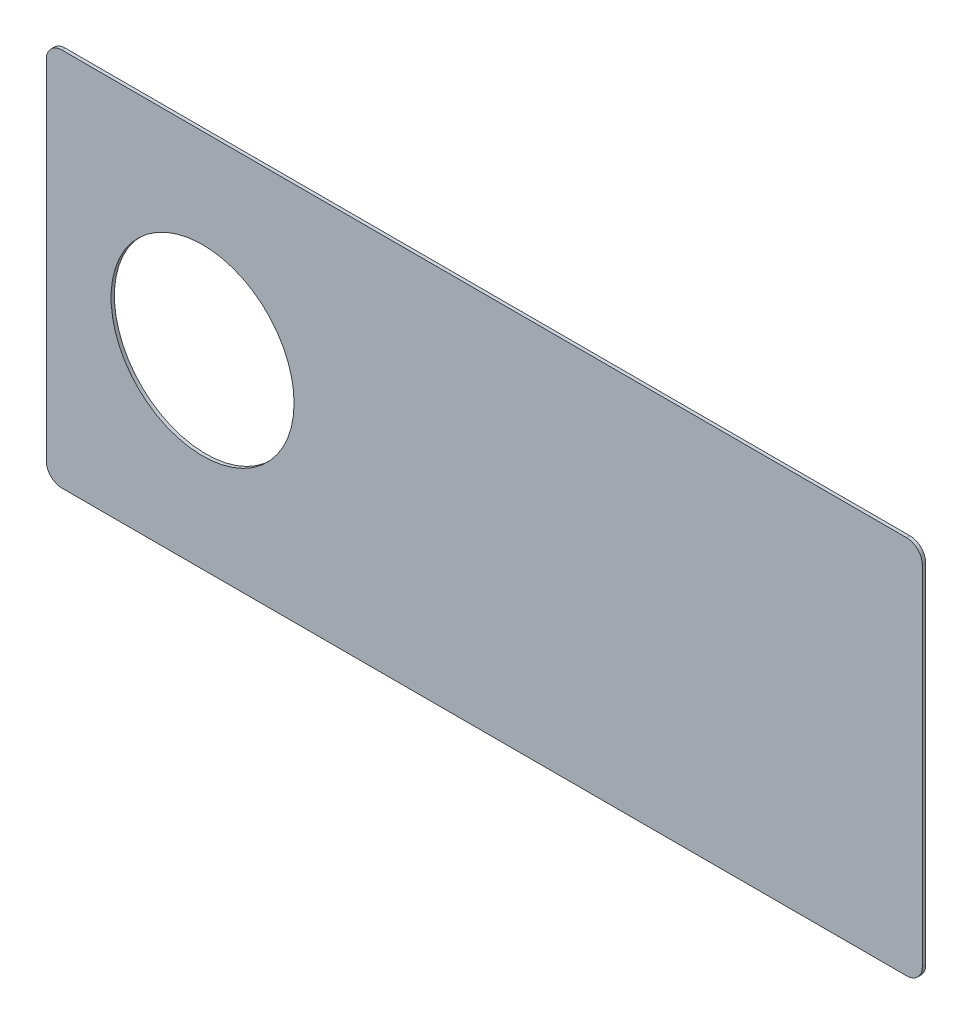
SolidWorks part; units mm, degrees
material "6061-T6 (SS)"
ref_plane "Front Plane" through (0, 0, 0) normal (0, 0, 1) x (1, 0, 0)
ref_plane "Top Plane" through (0, 0, 0) normal (0, 1, 0) x (1, 0, 0)
ref_plane "Right Plane" through (0, 0, 0) normal (1, 0, 0) x (0, 0, -1)
sketch "Extrude sketch 1" plane through (0, 0, 0) normal (0, 0, 1) x (1, 0, 0)
  line L0 (871, 170) -> (114, 170)
  line L1 (100, 156) -> (100, -156)
  line L2 (114, -170) -> (871, -170)
  line L3 (885, -156) -> (885, 156)
  arc A0 (114, 170) -> (100, 156) centre (114, 156) ccw
  arc A1 (100, -156) -> (114, -170) centre (114, -156) ccw
  arc A2 (871, -170) -> (885, -156) centre (871, -156) ccw
  arc A3 (885, 156) -> (871, 170) centre (871, 156) ccw
  circle A4 centre (240, 0) radius 82
  dimension "D1" = 164
  dimension "D2" = 14
  dimension "D3" = 645
  dimension "D4" = 785
  dimension "D5" = 170
  dimension "D6" = 340
extrude "Extrude 1" add sketch "Extrude sketch 1" along normal blind 3 from offset 300 separate body
